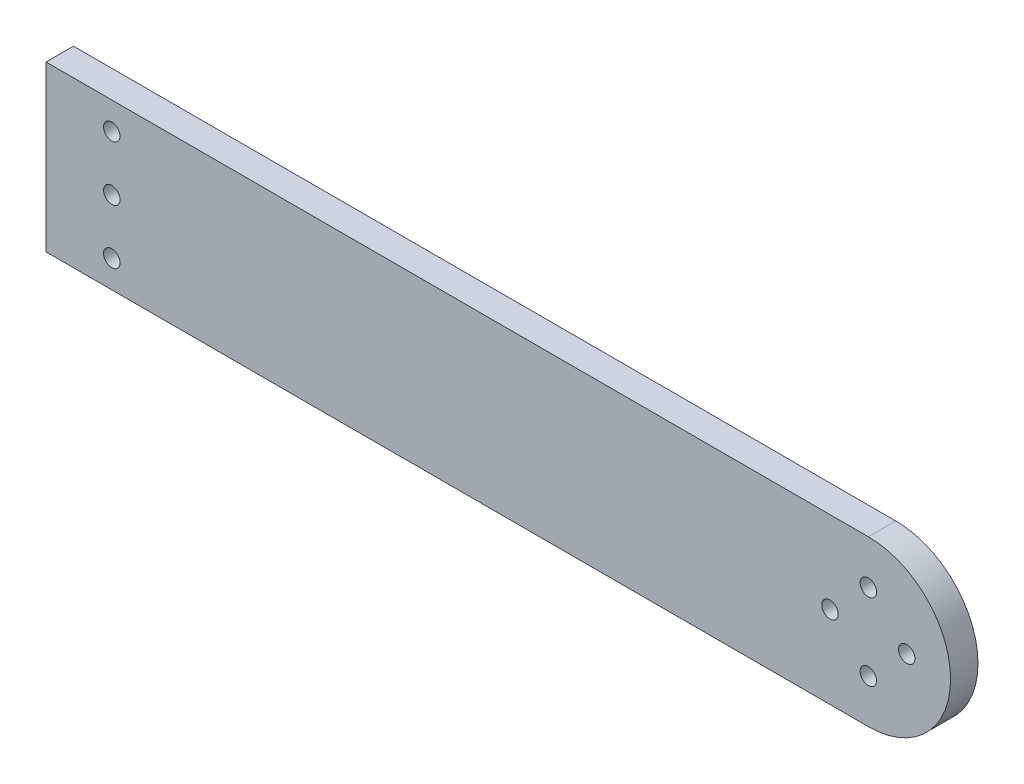
SolidWorks part; units mm, degrees
ref_plane "Front Plane" through (0, 0, 0) normal (0, 0, 1) x (1, 0, 0)
ref_plane "Top Plane" through (0, 0, 0) normal (0, 1, 0) x (1, 0, 0)
ref_plane "Right Plane" through (0, 0, 0) normal (1, 0, 0) x (0, 0, -1)
sketch "Sketch1" plane through (0, 0, 0) normal (0, 0, 1) x (1, 0, 0)
  line L0 (-135.9395, 0) -> (150.0902, 0) construction
  line L1 (75, 14.8359) -> (75, -15.8561) construction
  line L2 (75, -15) -> (-75, -15)
  line L4 (75, 15) -> (-75, 15)
  line L5 (-75, -15) -> (-75, 15)
  line L6 (75, -15) -> (-75, 15) construction
  line L7 (75, 15) -> (-75, -15) construction
  line L8 (82, 16.5985) -> (82, -12.6098) construction
  line L9 (-63, 15) -> (-63, -15) construction
  circle A0 centre (75, 0) radius 10 construction
  circle A1 centre (75, 7) radius 1.5
  circle A2 centre (82, 0) radius 1.5
  circle A3 centre (68, 0) radius 1.5
  circle A4 centre (75, -7) radius 1.5
  arc A5 (75, -15) -> (75, 15) centre (75, 0) ccw
  circle A6 centre (-63, 0) radius 1.5
  circle A9 centre (-63, 10) radius 1.5
  circle A10 centre (-63, -10) radius 1.5
  point P3 (0, 0)
  dimension "D1" = 20
  dimension "D4" = 3
  dimension "D6" = 3
  dimension "D9" = 30
  dimension "D11" = 3
  dimension "D13" = 10
  dimension "D2" = 75
  dimension "D3" = 7
  dimension "D5" = 7
  dimension "D7" = 30
  dimension "D8" = 150
  dimension "D10" = 12
  dimension "D12" = 10
extrude "Boss-Extrude1" add sketch "Sketch1" along normal blind 5
